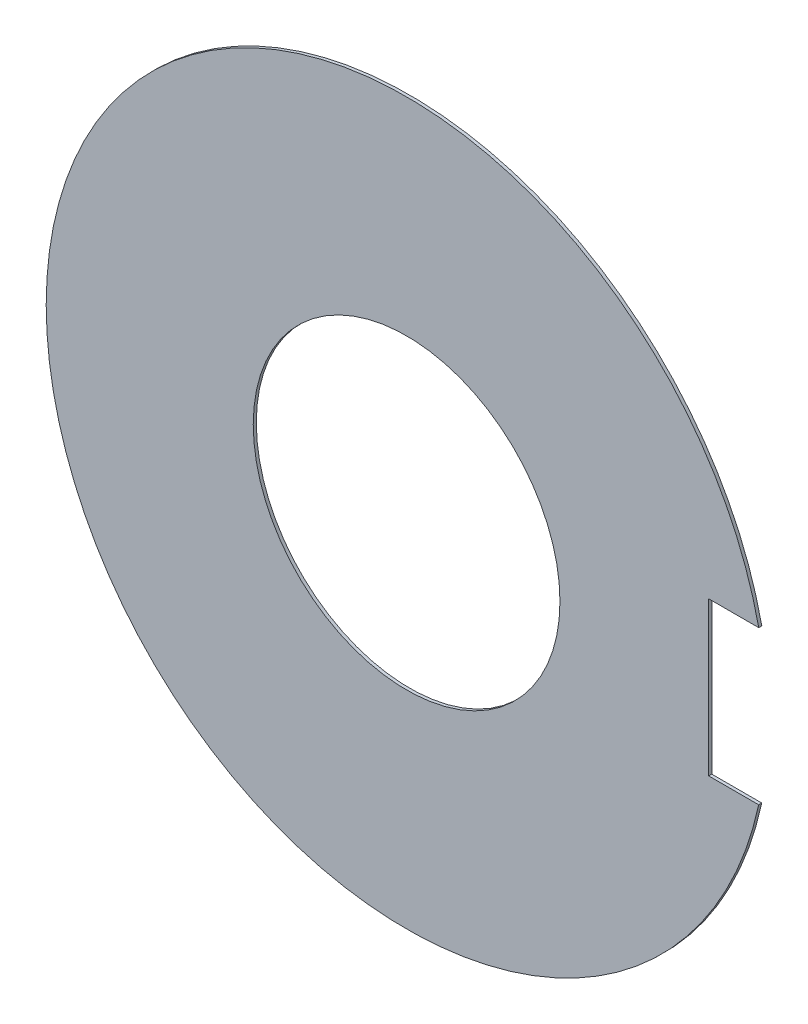
SolidWorks part; units mm, degrees
material "PTFE (general)"
ref_plane "Front Plane" through (0, 0, 0) normal (0, 0, 1) x (1, 0, 0)
ref_plane "Top Plane" through (0, 0, 0) normal (0, 1, 0) x (1, 0, 0)
ref_plane "Right Plane" through (0, 0, 0) normal (1, 0, 0) x (0, 0, -1)
sketch "Sketch1" plane through (0, 0, 0) normal (0, 0, 1) x (1, 0, 0)
  circle A0 centre (0, 0) radius 12.7
  circle A1 centre (0, 0) radius 29.845
  dimension "D1" = 59.69
  dimension "D2" = 25.4
extrude "Boss-Extrude1" add sketch "Sketch1" along normal blind 0.254
sketch "Sketch2" plane through (0, 0, 0.254) normal (0, 0, 1) x (1, 0, 0)
  line L1 (25.019, 6.35) -> (31.7642, 6.35)
  line L2 (25.019, 6.35) -> (25.019, -6.352)
  line L3 (25.019, -6.352) -> (31.7642, -6.352)
  line L4 (31.7642, 6.35) -> (31.7642, -6.352)
  dimension "D1" = 12.702
  dimension "D2" = 25.019
  dimension "D3" = 31.7642
extrude "Cut-Extrude1" cut sketch "Sketch2" against normal through all
